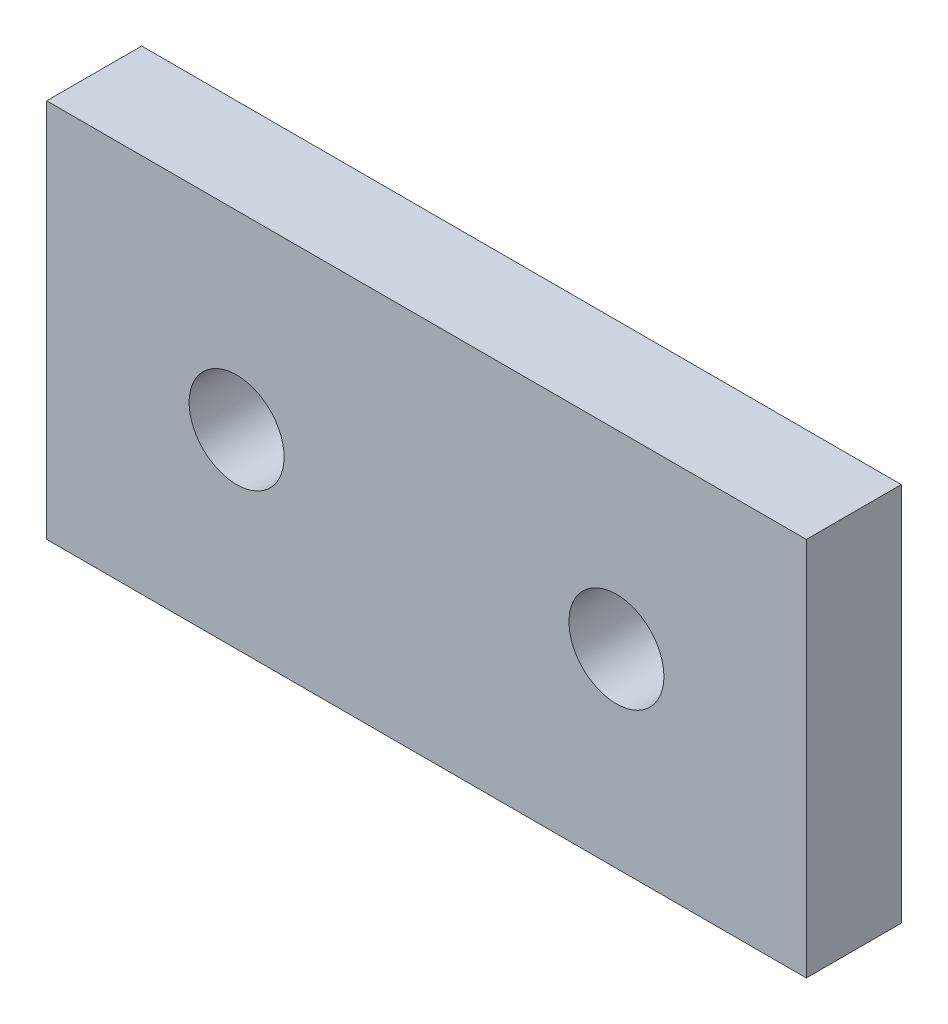
SolidWorks part; units mm, degrees
ref_plane "前视基准面" through (0, 0, 0) normal (0, 0, 1) x (1, 0, 0)
ref_plane "上视基准面" through (0, 0, 0) normal (0, 1, 0) x (1, 0, 0)
ref_plane "右视基准面" through (0, 0, 0) normal (1, 0, 0) x (0, 0, -1)
ref_plane "基准面1" through (0, 0, -5) normal (0, 0, 1) x (1, 0, 0)
sketch "草图1" plane through (0, 0, -5) normal (0, 0, 1) x (1, 0, 0)
  line L0 (0, 0) -> (80, 0)
  line L1 (80, 0) -> (80, 40)
  line L2 (80, 40) -> (0, 40)
  line L3 (0, 40) -> (0, 0)
extrude "凸台-拉伸1" add sketch "草图1" along normal blind 10
ref_plane "基准面2" through (0, 0, 5) normal (0, 0, 1) x (1, 0, 0)
sketch "草图2" plane through (0, 0, 5) normal (0, 0, 1) x (1, 0, 0)
  circle A0 centre (20, 20) radius 5
  circle A1 centre (60, 20) radius 5
extrude "切除-拉伸1" cut sketch "草图2" against normal through all
